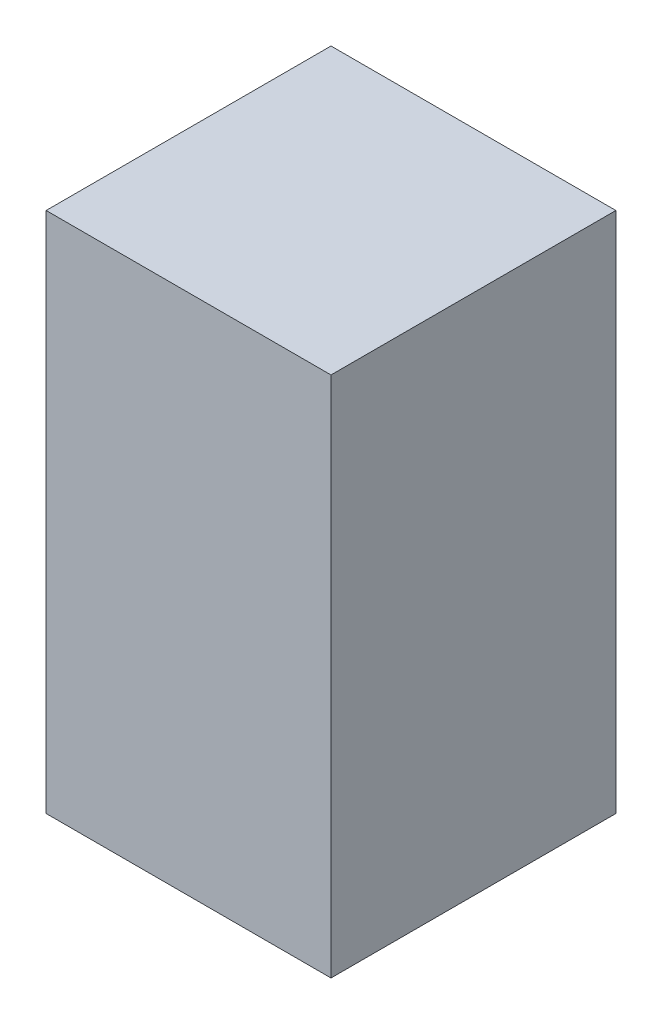
SolidWorks part; units mm, degrees
ref_plane "Front Plane" through (0, 0, 0) normal (0, 0, 1) x (1, 0, 0)
ref_plane "Top Plane" through (0, 0, 0) normal (0, 1, 0) x (1, 0, 0)
ref_plane "Right Plane" through (0, 0, 0) normal (1, 0, 0) x (0, 0, -1)
sketch "Sketch1" plane through (0, 0, 0) normal (0, 1, 0) x (1, 0, 0)
  line L1 (0, 0) -> (12, 0)
  line L2 (0, 0) -> (0, 12)
  line L3 (0, 12) -> (12, 12)
  line L4 (12, 0) -> (12, 12)
  dimension "D1" = 12
extrude "Boss-Extrude1" add sketch "Sketch1" along normal blind 22
